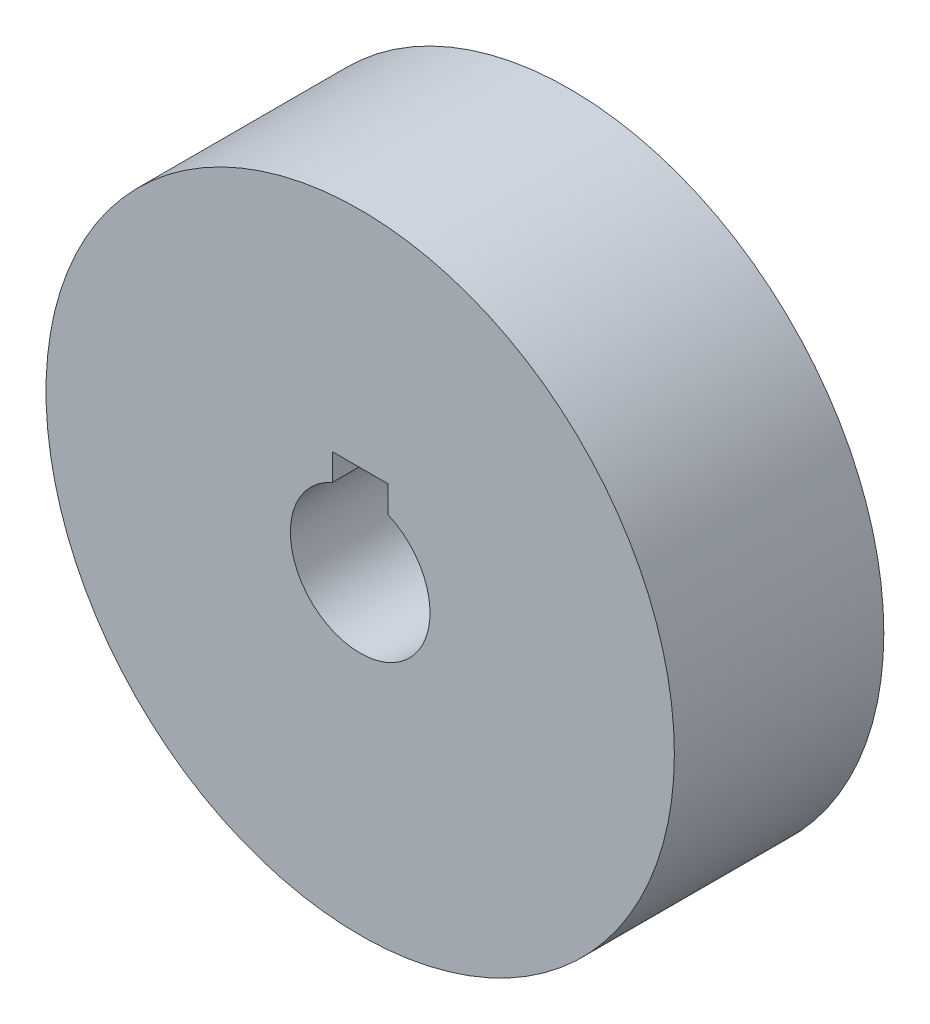
SolidWorks part; units mm, degrees
ref_plane "Front Plane" through (0, 0, 0) normal (0, 0, 1) x (1, 0, 0)
ref_plane "Top Plane" through (0, 0, 0) normal (0, 1, 0) x (1, 0, 0)
ref_plane "Right Plane" through (0, 0, 0) normal (1, 0, 0) x (0, 0, -1)
sketch "Sketch1" plane through (0, 0, 0) normal (0, 0, 1) x (1, 0, 0)
  line L0 (4, 9.1652) -> (4, 13)
  line L1 (4, 13) -> (-4, 13)
  line L2 (-4, 13) -> (-4, 9.1652)
  circle A0 centre (0, 0) radius 45
  arc A1 (-4, 9.1652) -> (4, 9.1652) centre (0, 0) ccw
  point P8 (0, 13)
  dimension "D1" = 90
  dimension "D2" = 20
  dimension "D3" = 8
  dimension "D4" = 23
extrude "Boss-Extrude1" add sketch "Sketch1" along normal blind 30
